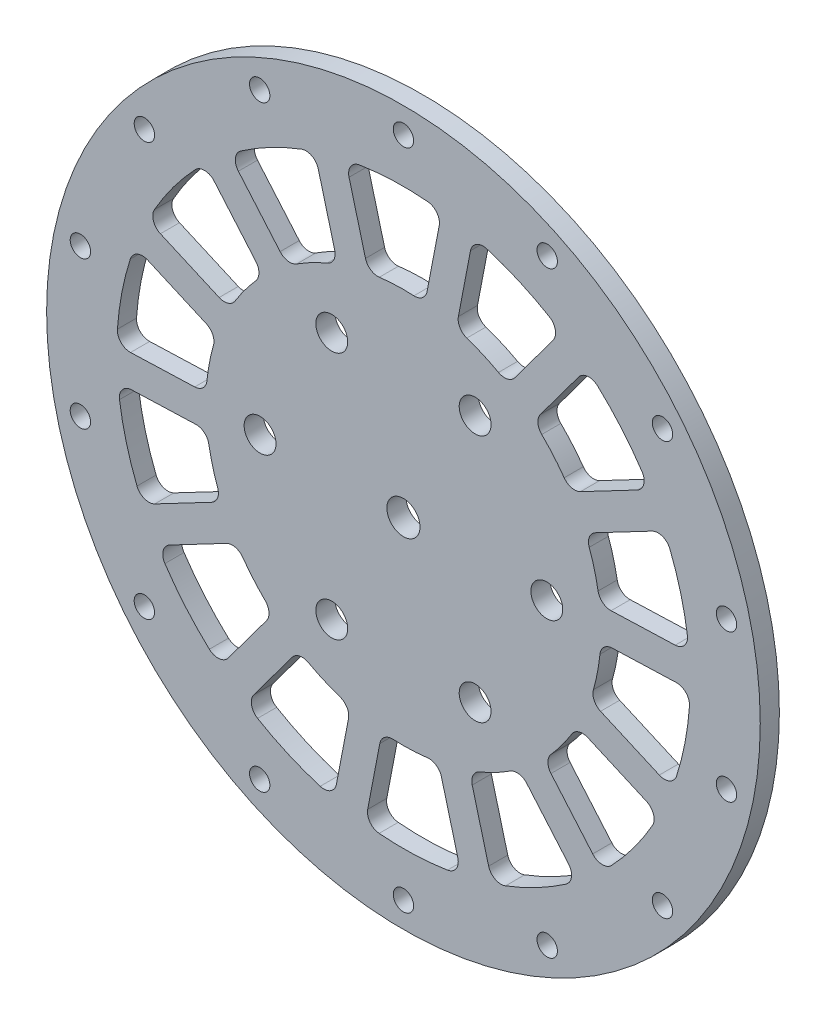
SolidWorks part; units mm, degrees
material "Thornel Mat VMA"
ref_plane "Front Plane" through (0, 0, 0) normal (0, 0, 1) x (1, 0, 0)
ref_plane "Top Plane" through (0, 0, 0) normal (0, 1, 0) x (1, 0, 0)
ref_plane "Right Plane" through (0, 0, 0) normal (1, 0, 0) x (0, 0, -1)
other "Configuration Table"
sketch "草图1" plane through (0, 0, 0) normal (0, 0, 1) x (1, 0, 0)
  circle A0 centre (0, 0) radius 52 construction
  circle A1 centre (0, 52) radius 1.6
  circle A2 centre (22.562, 46.8504) radius 1.6
  circle A3 centre (40.6552, 32.4215) radius 1.6
  circle A4 centre (50.6963, 11.5711) radius 1.6
  circle A5 centre (50.6963, -11.5711) radius 1.6
  circle A6 centre (40.6552, -32.4215) radius 1.6
  circle A7 centre (22.562, -46.8504) radius 1.6
  circle A8 centre (0, -52) radius 1.6
  circle A9 centre (-22.562, -46.8504) radius 1.6
  circle A10 centre (-40.6552, -32.4215) radius 1.6
  circle A11 centre (-50.6963, -11.5711) radius 1.6
  circle A12 centre (-50.6963, 11.5711) radius 1.6
  circle A13 centre (-40.6552, 32.4215) radius 1.6
  circle A14 centre (-22.562, 46.8504) radius 1.6
  circle A15 centre (0, 0) radius 56
  circle A16 centre (0, 0) radius 2.6
  point P34 (0, 0)
  line B0 (16.75, 19.4856) -> (16.75, -19.4856)
  line B1 (-24.0925, -5.2644) -> (-16.75, -7.4856)
  line B2 (-24.0925, 5.2644) -> (-16.75, 7.4856)
  line B3 (2.5, 13.3301) -> (2.5, 4.3301)
  line B4 (2.5, 13.3301) -> (6.223, 21.7171)
  line B5 (-2.5, 13.3301) -> (-2.5, 4.3301)
  line B6 (-2.5, 13.3301) -> (-6.223, 21.7171)
  line B7 (-16.75, 19.4856) -> (-16.75, -19.4856)
  line B8 (-2.5, -13.3301) -> (-2.5, -4.3301)
  line B9 (-2.5, -13.3301) -> (-6.223, -21.7171)
  line B10 (2.5, -13.3301) -> (6.223, -21.7171)
  line B11 (2.5, -13.3301) -> (2.5, -4.3301)
  line B12 (24.0925, 5.2644) -> (16.75, 7.4856)
  line B13 (24.0925, -5.2644) -> (16.75, -7.4856)
  circle B14 centre (11.25, 19.4856) radius 2.5
  circle B15 centre (-11.25, 19.4856) radius 2.5
  circle B16 centre (-22.5, 0) radius 2.5
  circle B17 centre (0, 0) radius 5
  circle B18 centre (22.5, 0) radius 5.5
  circle B19 centre (11.25, 19.4856) radius 5.5
  circle B20 centre (-11.25, 19.4856) radius 5.5
  circle B21 centre (-22.5, 0) radius 5.5
  circle B22 centre (-11.25, -19.4856) radius 2.5
  circle B23 centre (11.25, -19.4856) radius 2.5
  circle B24 centre (22.5, 0) radius 2.5
  circle B25 centre (-11.25, -19.4856) radius 5.5
  circle B26 centre (11.25, -19.4856) radius 5.5
  dimension "D1" = 104
  dimension "D2" = 3.2
  dimension "D4" = 112
  dimension "D5" = 5.2
  dimension "D3" = 14
sketch_block_instance "块1-1"
sketch_block "块1"
extrude "凸台-拉伸1" add sketch "草图1" along normal blind 3 contours A15 B26 B10 B11 B17 B8 B9 B25 B7 B1 B21 B2 B20 B6 B5 B3 B4 B19 B0 B12 B18 B13 A1 A2 A3 A4 A5 A6 A7 A8 A9 A10 A11 A12 | B25 B9 B8 B17 B5 B6 B20 B7 | B26 B0 B19 B4 B3 B17 B11 B10 | B19 B14 | B18 B24 | B18 B12 B0 B13 | B26 B23 | B25 B22 | B20 B15 | B21 B1 B7 B2 | B21 B16 | B17 A16
sketch "草图2" plane through (0, 0, 3) normal (0, 0, 1) x (1, 0, 0)
  circle A0 centre (0, 0) radius 45
  circle A1 centre (0, 0) radius 31
  dimension "D1" = 62
  dimension "D2" = 90
extrude "切除-拉伸1" cut sketch "草图2" against normal blind 10
sketch "草图3" plane through (0, 0, 3) normal (0, 0, 1) x (1, 0, 0)
  line L0 (5.8477, 30.4435) -> (15.0265, 28.6803) construction
  line L14 (-12.1927, 46.014) -> (-6.887, 25.991)
  line L15 (8.9795, 46.7474) -> (5.0721, 26.4052)
  line L16 (28.3732, 38.2219) -> (16.0266, 21.5896)
  line L17 (42.1472, 22.1261) -> (23.8068, 12.4979)
  line L18 (47.5735, 1.6479) -> (26.8718, 0.9308)
  line L19 (43.5772, -19.1566) -> (24.6145, -10.8206)
  line L20 (30.95, -36.167) -> (17.4821, -20.4289)
  line L21 (12.1927, -46.014) -> (6.887, -25.991)
  line L22 (-8.9795, -46.7474) -> (-5.0721, -26.4052)
  line L23 (-28.3732, -38.2219) -> (-16.0266, -21.5896)
  line L24 (-42.1472, -22.1261) -> (-23.8068, -12.4979)
  line L25 (-47.5735, -1.6479) -> (-26.8718, -0.9308)
  line L26 (-43.5772, 19.1566) -> (-24.6145, 10.8206)
  line L27 (-30.95, 36.167) -> (-17.4821, 20.4289)
  circle A0 centre (0, 0) radius 31 construction
  point P3 (0, 0)
  point P30 (0, 0)
  point P36 (0, 0)
  point P39 (0, 0)
  point P42 (0, 0)
  point P45 (0, 0)
  point P48 (0, 0)
  point P51 (0, 0)
  point P54 (0, 0)
  point P57 (0, 0)
  point P60 (0, 0)
  point P63 (0, 0)
  point P66 (0, 0)
  point P69 (0, 0)
  point P72 (0, 0)
  dimension "D2" = 14
extrude "拉伸-薄壁1" add sketch "草图3" against normal up to surface (3 mm away) thin up to face at (13.75, -19.4856, 0) thin type mid plane wall 5
fillet "圆角2" radius 2 56 edges at (10.9307, 43.6523, 1.5) (3.3736, 30.8159, 1.5) (6.0204, 44.5955, 1.5) (-5.4978, 30.5086, 1.5) (-10.331, 29.2279, 1.5) (-9.0918, 44.072, 1.5) (28.7882, 34.5867, 1.5) (8.2838, 29.8727, 1.5) (24.7735, 37.5669, 1.5) (16.41, 26.3004, 1.5) (40.9439, 18.6708, 1.5) (20.4247, 23.3202, 1.5) (38.6198, 23.0978, 1.5) (26.1962, 16.5758, 1.5) (44.9901, -0.9431, 1.5) (28.5203, 12.1488, 1.5) (44.817, 4.0539, 1.5) (30.794, 3.5682, 1.5) (40.1255, -20.3702, 1.5) (30.9671, -1.4288, 1.5) (42.1377, -15.7929, 1.5) (29.2926, -10.1462, 1.5) (27.3136, -35.7627, 1.5) (27.2804, -14.7234, 1.5) (31.1125, -32.5118, 1.5) (21.9894, -21.851, 1.5) (9.0918, -44.072, 1.5) (18.1905, -25.1019, 1.5) (13.925, -42.7913, 1.5) (10.331, -29.2279, 1.5) (-10.9307, -43.6523, 1.5) (5.4978, -30.5086, 1.5) (-6.0204, -44.5955, 1.5) (-3.3736, -30.8159, 1.5) (-28.7882, -34.5867, 1.5) (-8.2838, -29.8727, 1.5) (-24.7735, -37.5669, 1.5) (-16.41, -26.3004, 1.5) (-40.9439, -18.6708, 1.5) (-20.4247, -23.3202, 1.5) (-38.6198, -23.0978, 1.5) (-26.1962, -16.5758, 1.5) (-44.9901, 0.9431, 1.5) (-28.5203, -12.1488, 1.5) (-30.794, -3.5682, 1.5) (-40.1255, 20.3702, 1.5) (-30.9671, 1.4288, 1.5) (-42.1377, 15.7929, 1.5) (-29.2926, 10.1462, 1.5) (-13.925, 42.7913, 1.5) (-18.1905, 25.1019, 1.5) (-27.3136, 35.7627, 1.5) (-27.2804, 14.7234, 1.5) (-31.1125, 32.5118, 1.5) (-21.9894, 21.851, 1.5) (-44.817, -4.0539, 1.5)
sketch "草图4" plane through (0, 0, 3) normal (0, 0, 1) x (1, 0, 0)
  circle A0 centre (0, 0) radius 37.9682
extrude "拉伸-薄壁2" [suppressed] add sketch "草图4" against normal blind 4 thin
fillet "圆角3" [suppressed] radius 1
sketch "草图5" plane through (0, 0, 3) normal (0, 0, 1) x (1, 0, 0)
  circle B0 centre (0, 0) radius 56
  circle B1 centre (-22.5, 0) radius 2.5
  circle B2 centre (-11.25, -19.4856) radius 2.5
  circle B3 centre (11.25, -19.4856) radius 2.5
  circle B4 centre (22.5, 0) radius 2.5
  circle B5 centre (11.25, 19.4856) radius 2.5
  circle B6 centre (-11.25, 19.4856) radius 2.5
sketch_block_instance "块2-1"
sketch_block "块2"
